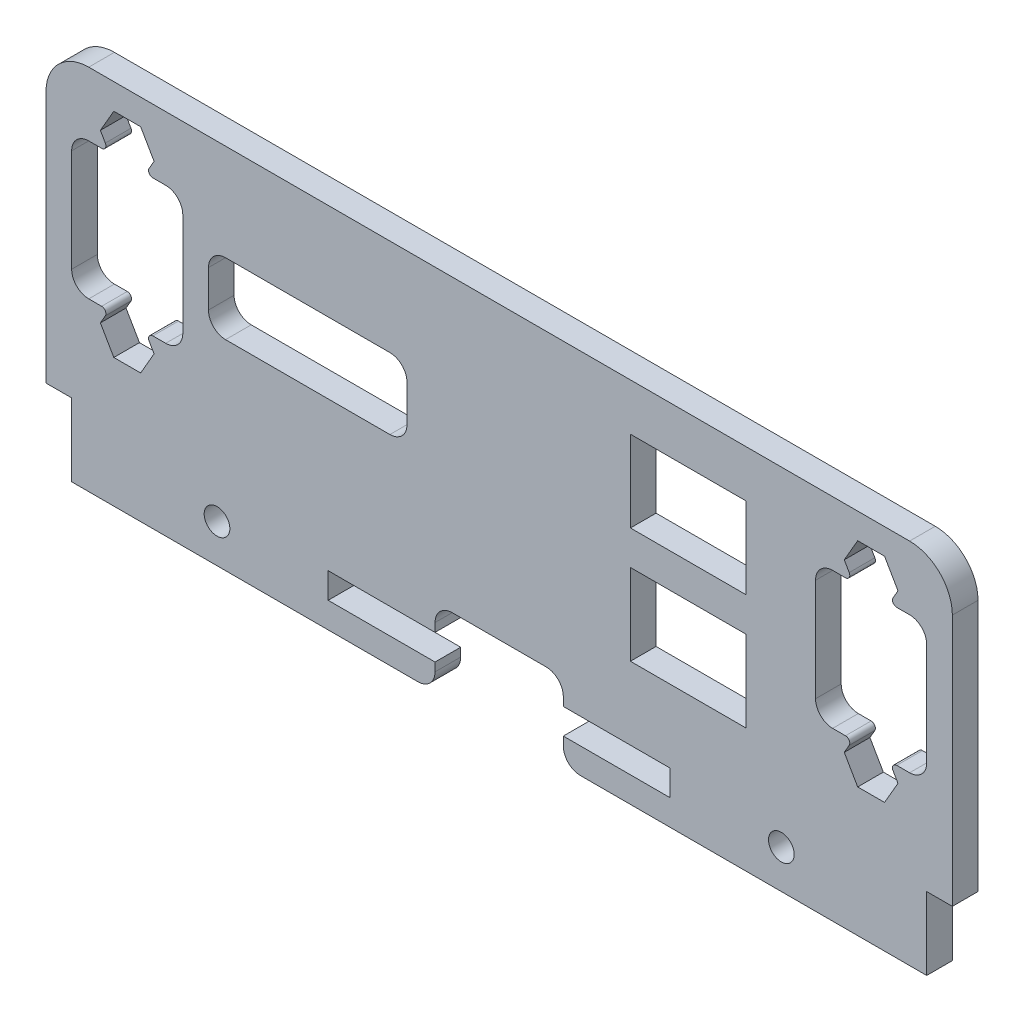
SolidWorks part; units mm, degrees
other "Marcação1"
sketch "Esboço7" plane through (-68, 31.5, 3) normal (-0.6758, 0.2828, 0.6807) x (0.7271, 0.1043, 0.6785)
sketch "Esboço8" plane through (-68, 31.5, 3) normal (-0.6758, 0.2828, 0.6807) x (0.7271, 0.1043, 0.6785)
sketch "Esboço9" plane through (-60.5, 31.5, 3) normal (-0.6758, 0.2828, 0.6807) x (0.7271, 0.1043, 0.6785)
sketch "Esboço12" plane through (-60.5, 31.5, 3) normal (-0.6758, 0.2828, 0.6807) x (0.7271, 0.1043, 0.6785)
sketch "Esboço14" plane through (-60.5, 31.5, 3) normal (-0.6758, 0.2828, 0.6807) x (0.7271, 0.1043, 0.6785)
sketch "Esboço15" plane through (-60.5, 36.25, 3) normal (-0.6758, 0.2828, 0.6807) x (0.7271, 0.1043, 0.6785)
sketch "Esboço18" plane through (-60.5, 33.25, 3) normal (-0.6758, 0.2828, 0.6807) x (0.7271, 0.1043, 0.6785)
sketch "Esboço20" plane through (-60.5, 29.8, 3) normal (-0.6758, 0.2828, 0.6807) x (0.7271, 0.1043, 0.6785)
sketch "Esboço22" plane through (-60.5, 29.8, 3) normal (-0.6758, 0.2828, 0.6807) x (0.7271, 0.1043, 0.6785)
sketch "Sketch10" plane through (-53, 21.5, 1.5) normal (-0.6758, 0.2828, 0.6807) x (0.7271, 0.1043, 0.6785)
sketch "Sketch14" plane through (-53, 21.5, 1.5) normal (-0.6758, 0.2828, 0.6807) x (0.7271, 0.1043, 0.6785)
sketch "Sketch15" plane through (-53, 21.5, 1.5) normal (-0.6758, 0.2828, 0.6807) x (0.7271, 0.1043, 0.6785)
sketch "Sketch16" plane through (-53, 21.5, 1.5) normal (-0.6758, 0.2828, 0.6807) x (0.7271, 0.1043, 0.6785)
sketch "Sketch17" plane through (-53, 21.5, 1.5) normal (-0.6758, 0.2828, 0.6807) x (0.7271, 0.1043, 0.6785)
material "Acrylic (Medium-high impact)"
ref_plane "Plano frontal" through (0, 0, 0) normal (0, 0, 1) x (1, 0, 0)
ref_plane "Plano superior" through (0, 0, 0) normal (0, 1, 0) x (1, 0, 0)
ref_plane "Plano direito" through (0, 0, 0) normal (1, 0, 0) x (0, 0, -1)
sketch "Esboço1" plane through (0, 0, 0) normal (0, 0, 1) x (1, 0, 0)
  line L1 (-50, -21.5) -> (50, -21.5)
  line L2 (-50, -21.5) -> (-50, 21.5)
  line L3 (-50, 21.5) -> (50, 21.5)
  line L4 (50, -21.5) -> (50, 21.5)
  line L5 (-50, -21.5) -> (50, 21.5) construction
  line L6 (-50, 21.5) -> (50, -21.5) construction
  point P0 (0, 0)
  dimension "D1" = 100
  dimension "D2" = 43
extrude "Ressalto-extrusão1" add sketch "Esboço1" along normal mid plane 3
sketch "Esboço2" plane through (0, 0, 1.5) normal (0, 0, 1) x (1, 0, 0)
  line L21 (-20, -15.5) -> (-7.5, -15.5)
  line L22 (-20, -15.5) -> (-20, -18.5)
  line L23 (-20, -18.5) -> (-7.5, -18.5)
  line L24 (20, -15.5) -> (20, -18.5)
  line L25 (-20, -15.5) -> (20, -18.5) construction
  line L26 (-20, -18.5) -> (20, -15.5) construction
  line L27 (0, -1.65) -> (0, 1.65) construction
  line L30 (-7.5, -18.5) -> (-7.5, -21.5)
  line L31 (-7.5, -21.5) -> (7.5, -21.5)
  line L32 (7.5, -18.5) -> (7.5, -21.5)
  line L33 (-50, -21.5) -> (50, -21.5) construction
  line L34 (7.5, -18.5) -> (20, -18.5)
  line L37 (-7.5, -15.5) -> (-7.5, -12.5)
  line L38 (-7.5, -12.5) -> (7.5, -12.5)
  line L39 (7.5, -15.5) -> (7.5, -12.5)
  line L40 (7.5, -15.5) -> (20, -15.5)
  circle A2 centre (-33, -17) radius 1.5
  circle A4 centre (33, -17) radius 1.5
  point P13 (0, -21.5)
  point P14 (0, -17)
  dimension "D4" = 13
  dimension "D8" = 3
  dimension "D2" = 3
  dimension "D3" = 15
  dimension "D5" = 3
  dimension "D6" = 3
  dimension "D13" = 40
extrude "Corte-extrusão1" cut sketch "Esboço2" against normal through all
sketch "Sketch7" plane through (0, 0, 0) normal (0, 0, 1) x (1, 0, 0)
  line L0 (7.5, -15.5) -> (7.5, -12.5) construction
  line L1 (15.35, 2.5) -> (28.85, 2.5)
  line L2 (15.35, 2.5) -> (15.35, -7)
  line L3 (15.35, -7) -> (28.85, -7)
  line L4 (28.85, 2.5) -> (28.85, -7)
  line L17 (15.35, 16) -> (28.85, 16)
  line L18 (15.35, 16) -> (15.35, 6.5)
  line L19 (15.35, 6.5) -> (28.85, 6.5)
  line L20 (28.85, 16) -> (28.85, 6.5)
  line L21 (15.35, 6.5) -> (15.35, 2.5) construction
  line L25 (7.5, -12.5) -> (-7.5, -12.5) construction
  dimension "D1" = 13.5
  dimension "D2" = 9.5
  dimension "D3" = 4
  dimension "D4" = 7.85
  dimension "D5" = 23
  dimension "D6" = 5.5
extrude "Cut-Extrude6" cut sketch "Sketch7" against normal through all both and the other way through all
sketch "Sketch8" plane through (0, 0, 0) normal (0, 0, 1) x (1, 0, 0)
  line L9 (0, -1.65) -> (0, 1.65) construction
  line L10 (-50, 21.5) -> (-53, 21.5)
  line L11 (-50, 21.5) -> (-50, -13)
  line L12 (-50, -13) -> (-53, -13)
  line L13 (-53, 21.5) -> (-53, -13)
  line L14 (53, 21.5) -> (53, -13)
  line L15 (50, -13) -> (53, -13)
  line L16 (50, 21.5) -> (50, -13)
  line L17 (50, 21.5) -> (53, 21.5)
  line L18 (-50, -21.5) -> (-7.5, -21.5) construction
  dimension "D1" = 8.5
  dimension "D2" = 3
extrude "Boss-Extrude1" add sketch "Sketch8" along normal mid plane 3
fillet "Fillet3" radius 2 4 edges at (7.5, -12.5, 0) (-7.5, -12.5, 0) (7.5, -21.5, 0) (-7.5, -21.5, 0)
fillet "Fillet4" radius 5 2 edges at (53, 21.5, 0) (-53, 21.5, 0)
sketch "Sketch6" plane through (0, 0, 0) normal (0, 0, 1) x (1, 0, 0)
  line L0 (-53, 16.5) -> (-53, -13) construction
  line L15 (48, 21.5) -> (-48, 21.5) construction
  line L23 (0, -1.65) -> (0, 1.65) construction
  line B0 (-40.5, 14.0307) -> (-40.5043, 14.0307)
  line B1 (-37, 6.0307) -> (-37, 0.0307)
  line B2 (-39, -1.9693) -> (-40.5043, -1.9693)
  line B3 (-50, 12.0307) -> (-50, 0.0307)
  line B4 (-37, 6.0307) -> (-50, 6.0307) construction
  line B5 (-46.64, 15.7807) -> (-45.07, 18.5)
  line B6 (-45.07, 18.5) -> (-41.93, 18.5)
  line B7 (-41.93, 18.5) -> (-40.36, 15.7807)
  line B8 (-40.36, 15.7807) -> (-40.9374, 14.7807)
  line B9 (-46.0626, 14.7807) -> (-46.64, 15.7807)
  line B10 (-46.4957, 14.0307) -> (-48, 14.0307)
  line B11 (-46.0626, -2.7193) -> (-46.64, -3.7193)
  line B12 (-40.36, -3.7193) -> (-40.9374, -2.7193)
  line B13 (-41.93, -6.4386) -> (-40.36, -3.7193)
  line B14 (-45.07, -6.4386) -> (-41.93, -6.4386)
  line B15 (-46.64, -3.7193) -> (-45.07, -6.4386)
  line B16 (-46.4957, -1.9693) -> (-48, -1.9693)
  arc B17 (-45.855, 14.421) -> (-41.145, 14.421) centre (-43.5, 15.7807) cw construction
  arc B18 (-45.855, -2.3597) -> (-41.145, -2.3597) centre (-43.5, -3.7193) ccw construction
  arc B19 (-46.0626, -2.7193) -> (-46.4957, -1.9693) centre (-46.4957, -2.4693) ccw
  arc B20 (-40.9374, -2.7193) -> (-40.5043, -1.9693) centre (-40.5043, -2.4693) cw
  arc B21 (-46.4957, 14.0307) -> (-46.0626, 14.7807) centre (-46.4957, 14.5307) ccw
  arc B22 (-40.5043, 14.0307) -> (-40.9374, 14.7807) centre (-40.5043, 14.5307) cw
  arc B23 (-48, 14.0307) -> (-50, 12.0307) centre (-48, 12.0307) ccw
  arc B24 (-48, -1.9693) -> (-50, 0.0307) centre (-48, 0.0307) cw
  arc B25 (-37, 0.0307) -> (-39, -1.9693) centre (-39, 0.0307) cw
  arc B26 (-39, 14.0307) -> (-37, 12.0307) centre (-39, 12.0307) cw
  line B27 (-37, 12.0307) -> (-37, 6.0307)
  line B28 (-39, 14.0307) -> (-40.5, 14.0307)
  line B29 (40.5, 14.0307) -> (40.5043, 14.0307)
  line B30 (37, 6.0307) -> (37, 0.0307)
  line B31 (39, -1.9693) -> (40.5043, -1.9693)
  line B32 (50, 12.0307) -> (50, 0.0307)
  line B33 (37, 6.0307) -> (50, 6.0307) construction
  line B34 (46.64, 15.7807) -> (45.07, 18.5)
  line B35 (45.07, 18.5) -> (41.93, 18.5)
  line B36 (41.93, 18.5) -> (40.36, 15.7807)
  line B37 (40.36, 15.7807) -> (40.9374, 14.7807)
  line B38 (46.0626, 14.7807) -> (46.64, 15.7807)
  line B39 (46.4957, 14.0307) -> (48, 14.0307)
  line B40 (46.0626, -2.7193) -> (46.64, -3.7193)
  line B41 (40.36, -3.7193) -> (40.9374, -2.7193)
  line B42 (41.93, -6.4386) -> (40.36, -3.7193)
  line B43 (45.07, -6.4386) -> (41.93, -6.4386)
  line B44 (46.64, -3.7193) -> (45.07, -6.4386)
  line B45 (46.4957, -1.9693) -> (48, -1.9693)
  arc B46 (45.855, 14.421) -> (41.145, 14.421) centre (43.5, 15.7807) ccw construction
  arc B47 (45.855, -2.3597) -> (41.145, -2.3597) centre (43.5, -3.7193) cw construction
  arc B48 (46.0626, -2.7193) -> (46.4957, -1.9693) centre (46.4957, -2.4693) cw
  arc B49 (40.9374, -2.7193) -> (40.5043, -1.9693) centre (40.5043, -2.4693) ccw
  arc B50 (46.4957, 14.0307) -> (46.0626, 14.7807) centre (46.4957, 14.5307) cw
  arc B51 (40.5043, 14.0307) -> (40.9374, 14.7807) centre (40.5043, 14.5307) ccw
  arc B52 (48, 14.0307) -> (50, 12.0307) centre (48, 12.0307) cw
  arc B53 (48, -1.9693) -> (50, 0.0307) centre (48, 0.0307) ccw
  arc B54 (37, 0.0307) -> (39, -1.9693) centre (39, 0.0307) ccw
  arc B55 (39, 14.0307) -> (37, 12.0307) centre (39, 12.0307) ccw
  line B56 (37, 12.0307) -> (37, 6.0307)
  line B57 (39, 14.0307) -> (40.5, 14.0307)
  dimension "D1" = 3
  dimension "D2" = 3
sketch_block_instance "Corte Gy Completo-3"
sketch_block "Corte Gy Completo" parameters "D3"=0.5, "D4"=2, "D5"=0.5, "D1"=3.14, "D2"=19.5
sketch_block_instance "Corte Gy Completo-4"
extrude "Corte Gy-VL53L0" cut sketch "Sketch6" against normal through all both and the other way through all
sketch "Sketch9" plane through (0, 0, 0) normal (0, 0, 1) x (1, 0, 0)
  line L0 (-53, 16.5) -> (-53, -13) construction
  line L1 (-49.5, 17.5) -> (-38, 17.5)
  line L2 (-49.5, 17.5) -> (-49.5, 14.5)
  line L3 (-49.5, 14.5) -> (-38, 14.5)
  line L4 (-38, 17.5) -> (-38, 14.5)
  line L5 (48, 21.5) -> (-48, 21.5) construction
  line L8 (0, -1.65) -> (0, 1.65) construction
  line L9 (38, 17.5) -> (38, 14.5)
  line L10 (49.5, 14.5) -> (38, 14.5)
  line L11 (49.5, 17.5) -> (49.5, 14.5)
  line L12 (49.5, 17.5) -> (38, 17.5)
  circle A0 centre (-41.25, 6.7) radius 1.5
  circle A1 centre (46.25, 6.7) radius 1.5
  arc A4 (-48, 21.5) -> (-53, 16.5) centre (-48, 16.5) ccw construction
  point P7 (-43.75, 14.5)
  point P20 (43.75, 14.5)
  dimension "D1" = 3
  dimension "D4" = 2.5
  dimension "D7" = 4
  dimension "D8" = 2.5
  dimension "D3" = 7.8
  dimension "D9" = 7.8
  dimension "D2" = 3
  dimension "D5" = 11.5
  dimension "D6" = 3.5
  dimension "D10" = 3.1972
extrude "Corte Gy-53LDK" [suppressed] cut sketch "Sketch9" against normal through all both and the other way through all
sketch "Sketch11" plane through (0, 0, 1.5) normal (0, 0, 1) x (1, 0, 0)
  line L0 (-37, 0.0307) -> (-37, 12.0307) construction
  line L1 (-31, 7.2) -> (-13.78, 7.2) construction
  line L2 (-31, 7.2) -> (-31, 4.9) construction
  line L3 (-31, 4.9) -> (-13.78, 4.9) construction
  line L4 (-13.78, 7.2) -> (-13.78, 4.9) construction
  line L7 (-32, 10.2) -> (-12.78, 10.2)
  line L8 (-10.78, 8.2) -> (-10.78, 3.9)
  line L9 (-32, 1.9) -> (-12.78, 1.9)
  line L10 (-34, 8.2) -> (-34, 3.9)
  line L11 (-34, 10.2) -> (-10.78, 10.2) construction
  line L12 (-10.78, 10.2) -> (-10.78, 1.9) construction
  line L13 (-34, 1.9) -> (-10.78, 1.9) construction
  line L14 (-34, 10.2) -> (-34, 1.9) construction
  arc A0 (-12.78, 10.2) -> (-10.78, 8.2) centre (-12.78, 8.2) cw
  arc A1 (-10.78, 3.9) -> (-12.78, 1.9) centre (-12.78, 3.9) cw
  arc A2 (-32, 1.9) -> (-34, 3.9) centre (-32, 3.9) cw
  arc A3 (-32, 10.2) -> (-34, 8.2) centre (-32, 8.2) ccw
  point P19 (-10.78, 10.2)
  dimension "D7" = 2
  dimension "D1" = 1.9
  dimension "D2" = 2.3
  dimension "D3" = 13.78
  dimension "D4" = 3
  dimension "4" = 3
extrude "Cut-Extrude7" cut sketch "Sketch11" against normal through all both and the other way through all
